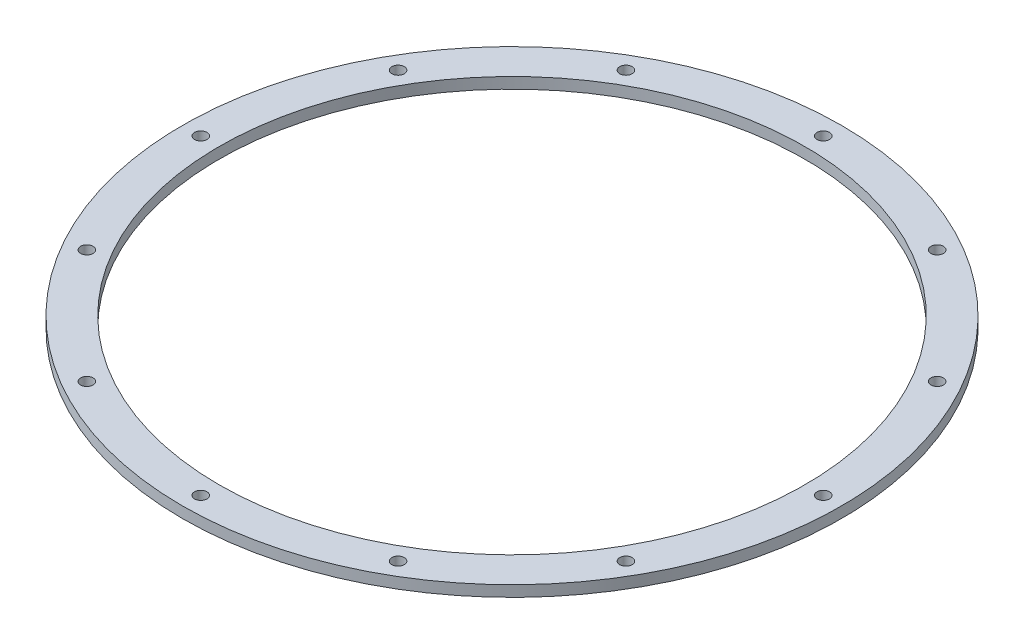
SolidWorks part; units mm, degrees
ref_plane "Front Plane" through (0, 0, 0) normal (0, 0, 1) x (1, 0, 0)
ref_plane "Top Plane" through (0, 0, 0) normal (0, 1, 0) x (1, 0, 0)
ref_plane "Right Plane" through (0, 0, 0) normal (1, 0, 0) x (0, 0, -1)
sketch "Sketch1" plane through (0, 0, 0) normal (0, 1, 0) x (1, 0, 0)
  circle A0 centre (0, 0) radius 80
  circle A1 centre (0, 0) radius 90
  circle A2 centre (0, 0) radius 85 construction
  circle A3 centre (0, 85) radius 1.7
  circle A4 centre (42.5, 73.6122) radius 1.7
  circle A5 centre (73.6122, 42.5) radius 1.7
  circle A6 centre (85, 0) radius 1.7
  circle A7 centre (73.6122, -42.5) radius 1.7
  circle A8 centre (42.5, -73.6122) radius 1.7
  circle A9 centre (0, -85) radius 1.7
  circle A10 centre (-42.5, -73.6122) radius 1.7
  circle A11 centre (-73.6122, -42.5) radius 1.7
  circle A12 centre (-85, 0) radius 1.7
  circle A13 centre (-73.6122, 42.5) radius 1.7
  circle A14 centre (-42.5, 73.6122) radius 1.7
  dimension "D1" = 160
  dimension "D2" = 180
  dimension "D3" = 170
  dimension "D4" = 3.4
  dimension "D5" = 12
extrude "Boss-Extrude1" add sketch "Sketch1" along normal blind 3 contours A1 A0
